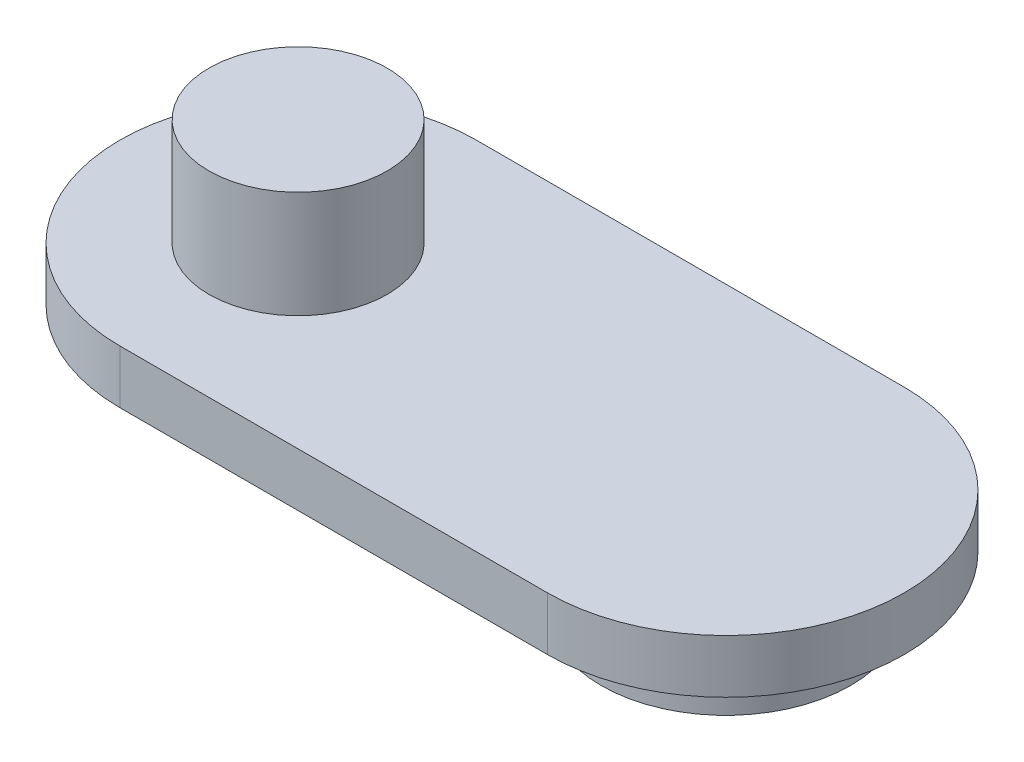
SolidWorks part; units mm, degrees
ref_plane "前视基准面" through (0, 0, 0) normal (0, 0, 1) x (1, 0, 0)
ref_plane "上视基准面" through (0, 0, 0) normal (0, 1, 0) x (1, 0, 0)
ref_plane "右视基准面" through (0, 0, 0) normal (1, 0, 0) x (0, 0, -1)
sketch "草图1" plane through (0, 0, 0) normal (0, 1, 0) x (1, 0, 0)
  line L0 (0, 0) -> (12, 0) construction
  line L1 (0, 5) -> (12, 5)
  line L2 (0, -5) -> (12, -5)
  arc A0 (0, 5) -> (0, -5) centre (0, 0) ccw
  arc A1 (12, -5) -> (12, 5) centre (12, 0) ccw
  point P3 (6, 0)
  dimension "D2" = 5
  dimension "D1" = 12
extrude "凸台-拉伸1" add sketch "草图1" along normal blind 1.5
sketch "草图2" plane through (0, 0, 0) normal (0, -1, 0) x (1, 0, 0)
  circle A0 centre (12, 0) radius 3.5
  dimension "D1" = 7
extrude "凸台-拉伸2" add sketch "草图2" along normal blind 1.5
sketch "草图3" plane through (0, 1.5, 0) normal (0, 1, 0) x (1, 0, 0)
  circle A0 centre (0, 0) radius 2.5
extrude "凸台-拉伸3" add sketch "草图3" along normal blind 3
